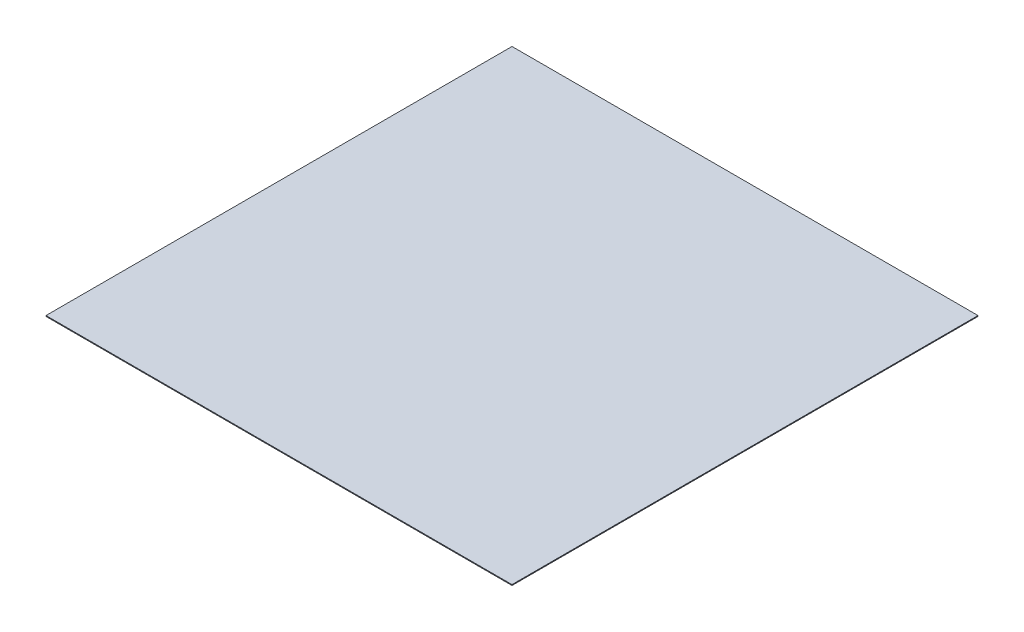
SolidWorks part; units mm, degrees
material "STYCAST 2850FT/Catalyst 23LV"
ref_plane "Front Plane" through (0, 0, 0) normal (0, 0, 1) x (1, 0, 0)
ref_plane "Top Plane" through (0, 0, 0) normal (0, 1, 0) x (1, 0, 0)
ref_plane "Right Plane" through (0, 0, 0) normal (1, 0, 0) x (0, 0, -1)
sketch "Sketch1" plane through (0, 0, 0) normal (0, 1, 0) x (1, 0, 0)
  line L1 (-69.85, -69.85) -> (69.85, -69.85)
  line L2 (-69.85, -69.85) -> (-69.85, 69.85)
  line L3 (-69.85, 69.85) -> (69.85, 69.85)
  line L4 (69.85, -69.85) -> (69.85, 69.85)
  line L5 (-69.85, -69.85) -> (69.85, 69.85) construction
  line L6 (-69.85, 69.85) -> (69.85, -69.85) construction
  line L7 (-50, -50) -> (50, -50) construction
  line L8 (-50, -50) -> (-50, 50) construction
  line L9 (-50, 50) -> (50, 50) construction
  line L10 (50, -50) -> (50, 50) construction
  line L11 (-50, -50) -> (50, 50) construction
  line L12 (-50, 50) -> (50, -50) construction
  point P0 (0, 0)
  point P6 (0, 0)
  dimension "D1" = 139.7
  dimension "D2" = 100
extrude "Boss-Extrude1" add sketch "Sketch1" along normal mid plane 0.25
equation "\"panel_width\"= 5.5in"
equation "\"finger_joint_width\"= 30mm"
equation "\"D1@Sketch1\"=\"panel_width\""
